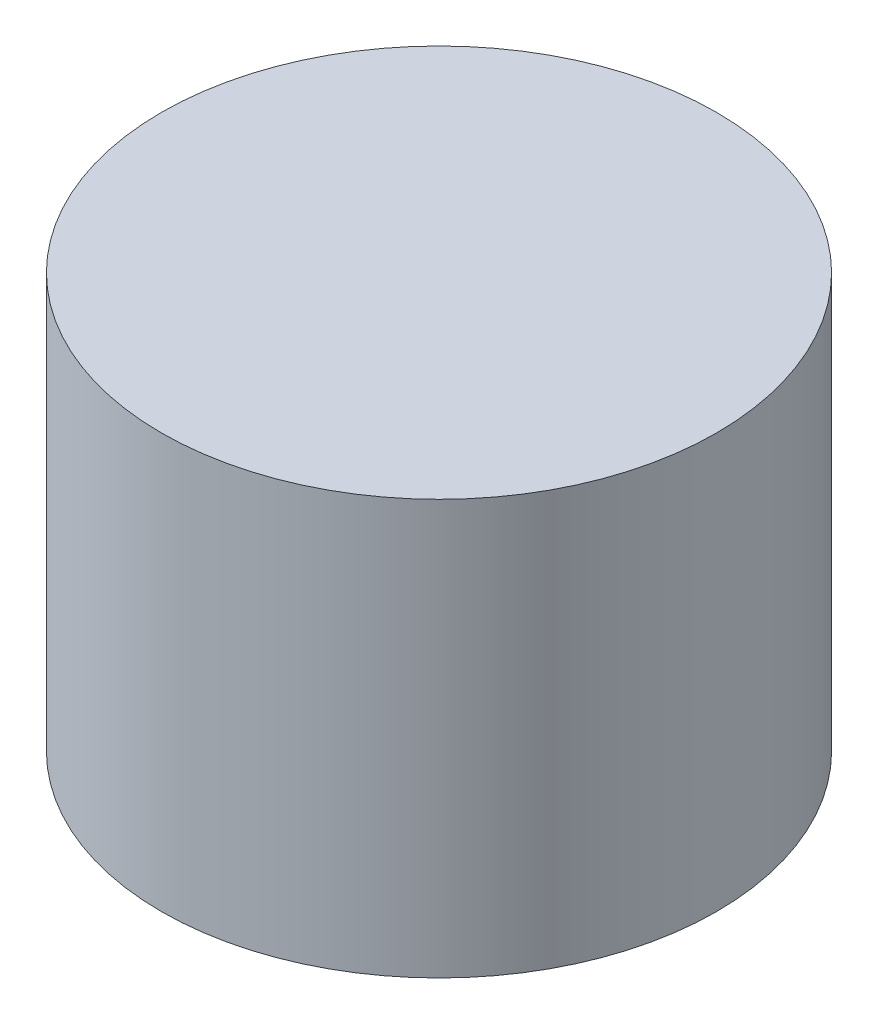
SolidWorks part; units mm, degrees
ref_plane "Front Plane" through (0, 0, 0) normal (0, 0, 1) x (1, 0, 0)
ref_plane "Top Plane" through (0, 0, 0) normal (0, 1, 0) x (1, 0, 0)
ref_plane "Right Plane" through (0, 0, 0) normal (1, 0, 0) x (0, 0, -1)
sketch "Sketch1" plane through (0, 0, 0) normal (0, 1, 0) x (1, 0, 0)
  circle A0 centre (0, 0) radius 7.5
  dimension "D1" = 15
extrude "Boss-Extrude1" add sketch "Sketch1" along normal blind 11.2
